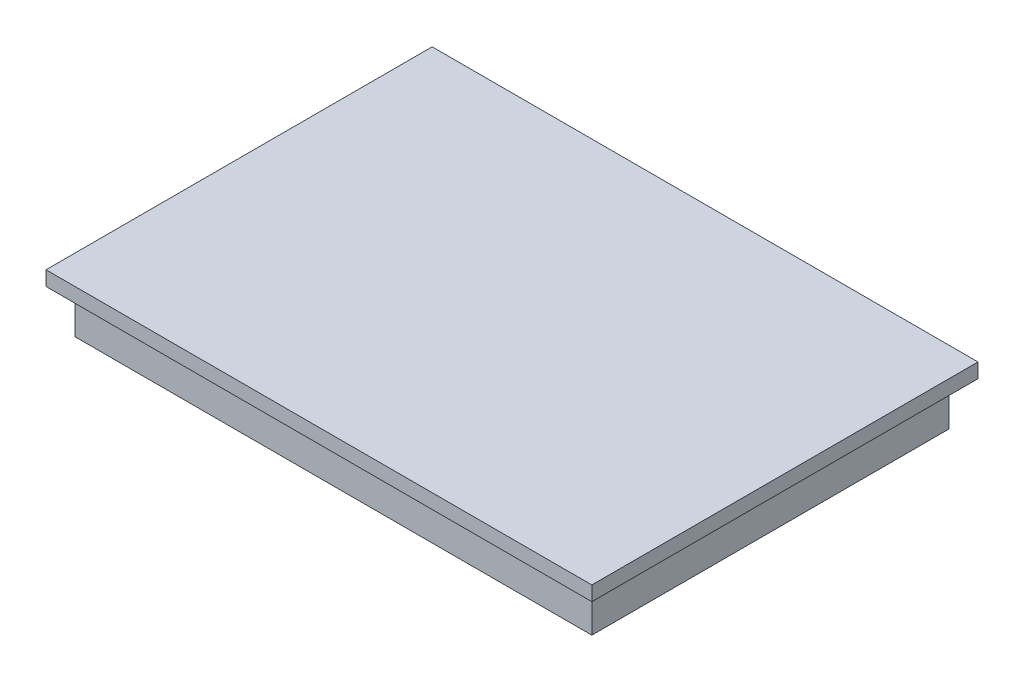
SolidWorks part; units mm, degrees
ref_plane "Front Plane" through (0, 0, 0) normal (0, 0, 1) x (1, 0, 0)
ref_plane "Top Plane" through (0, 0, 0) normal (0, 1, 0) x (1, 0, 0)
ref_plane "Right Plane" through (0, 0, 0) normal (1, 0, 0) x (0, 0, -1)
sketch "Sketch1" plane through (0, 0, 0) normal (0, 1, 0) x (1, 0, 0)
  line L0 (0, 0) -> (178, 0)
  line L1 (0, 0) -> (0, -123)
  line L2 (0, -123) -> (178, -123)
  line L3 (178, -123) -> (178, 0)
  line L4 (0, 0) -> (0, -5)
  line L5 (0, -5) -> (173, -5)
  line L6 (173, -5) -> (173, -118)
  line L7 (173, -118) -> (5, -118)
  line L8 (5, -118) -> (5, -5)
extrude "Boss-Extrude1" add sketch "Sketch1" along normal blind 20
sketch "Sketch2" plane through (0, 20, 0) normal (0, 1, 0) x (1, 0, 0)
  line L0 (0, 0) -> (0, 5)
  line L1 (0, 5) -> (183, 5)
  line L2 (183, 5) -> (183, -128)
  line L5 (-10, 5) -> (0, 5)
  line L6 (183, -128) -> (-5, -128)
  line L7 (-5, -128) -> (-5, 5)
extrude "Boss-Extrude4" add sketch "Sketch2" against normal blind 5
